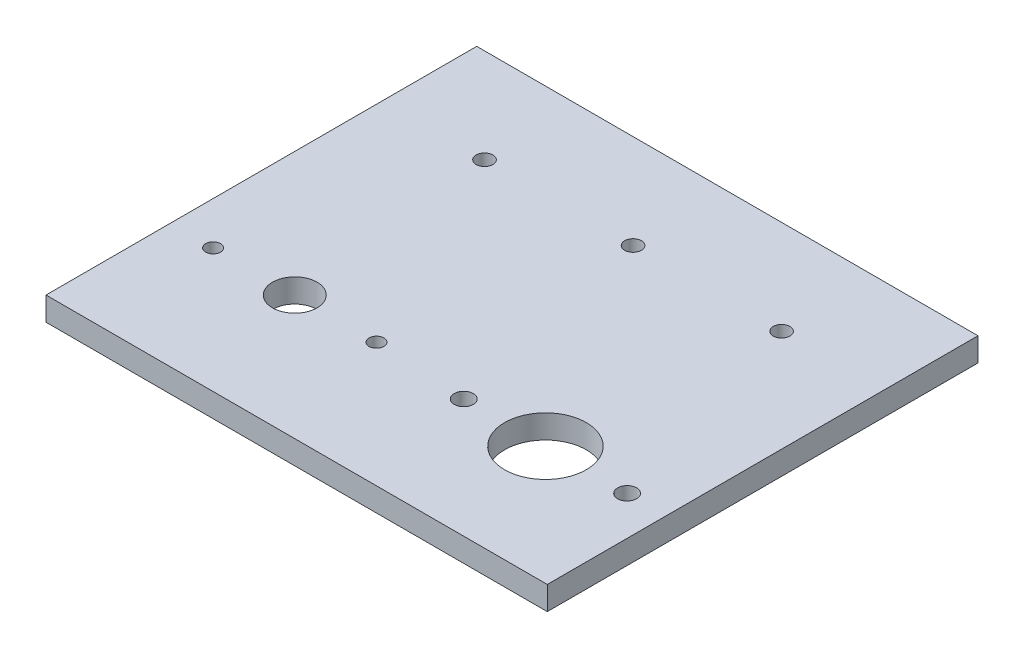
SolidWorks part; units mm, degrees
ref_plane "Front Plane" through (0, 0, 0) normal (0, 0, 1) x (1, 0, 0)
ref_plane "Top Plane" through (0, 0, 0) normal (0, 1, 0) x (1, 0, 0)
ref_plane "Right Plane" through (0, 0, 0) normal (1, 0, 0) x (0, 0, -1)
sketch "Sketch1" plane through (0, 0, 0) normal (0, 1, 0) x (1, 0, 0)
  line L1 (32.5, -58) -> (-32.5, -58)
  line L2 (32.5, -58) -> (32.5, 58)
  line L3 (32.5, 58) -> (-32.5, 58)
  line L4 (-32.5, -58) -> (-32.5, 58)
  line L5 (32.5, -58) -> (-32.5, 58) construction
  line L6 (32.5, 58) -> (-32.5, -58) construction
  line L7 (32.5, 7) -> (-32.5, 7) construction
  line L8 (32.5, 7) -> (32.5, 58) construction
  line L9 (32.5, 58) -> (-32.5, 58) construction
  line L10 (-32.5, 7) -> (-32.5, 58) construction
  line L11 (32.5, 7) -> (-32.5, 58) construction
  line L12 (32.5, 58) -> (-32.5, 7) construction
  line L13 (-102.5, -58) -> (-32.5, -58)
  line L14 (-102.5, -58) -> (-102.5, 58)
  line L15 (-102.5, 58) -> (-32.5, 58)
  line L16 (-32.5, -58) -> (-32.5, 58)
  line L17 (-102.5, -58) -> (-32.5, 58) construction
  line L18 (-102.5, 58) -> (-32.5, -58) construction
  point P0 (0, 0)
  point P6 (0, 32.5)
  point P7 (-67.5, 0)
  dimension "D1" = 51
  dimension "D2" = 65
  dimension "D3" = 65
  dimension "D4" = 70
extrude "Boss-Extrude1" add sketch "Sketch1" along normal blind 6.35 contours L4 L1 L2 L3 | L15 L14 L13 L4
sketch "Sketch2" plane through (0, 6.35, 0) normal (0, 1, 0) x (1, 0, 0)
  line L3 (32.5, -58) -> (-102.5, -58) construction
  circle A0 centre (0, -25.996) radius 22 construction
  circle A1 centre (-22, -25.996) radius 2.0193
  circle A2 centre (22, -25.996) radius 2.0193
  circle A3 centre (0, -25.996) radius 32.004 construction
  dimension "D1" = 44
  dimension "D2" = 64.008
  dimension "D3" = 4.0386
hole_wizard "#10 Clearance Hole1" positions "Sketch3" profile "Sketch4" hole size "#10" standard "ANSI Inch" end condition through all
sketch "Sketch3" plane through (0, 6.35, 0) normal (0, 1, 0) x (1, 0, 0)
  point P0 (-22, -25.996)
  point P3 (22, -25.996)
sketch "Sketch4" plane through (-22, 6.35, 25.996) normal (1, 0, 0) x (0, 0, 1)
  line L0 (0, 0) -> (0, 6.35)
  line L1 (0, 6.35) -> (2.5527, 6.35)
  line L2 (2.5527, 6.35) -> (2.5527, 0)
  line L5 (2.5527, 0) -> (0, 0)
  line L11 (0, -6.35) -> (0, 107.95) construction
  dimension "Thru Hole Dia." = 5.1054
  dimension "Thru Hole Depth" = 6.35
sketch "Sketch5" plane through (0, 6.35, 0) normal (0, 1, 0) x (1, 0, 0)
  line L0 (-75, 32.6) -> (-35, 32.6) construction
  line L1 (-35, 32.6) -> (5, 32.6) construction
  line L2 (32.5, 58) -> (-102.5, 58) construction
  point P9 (-35, 58)
  dimension "D1" = 40
  dimension "D2" = 40
  dimension "D3" = 25.4
sketch "Sketch9" plane through (0, 6.35, 0) normal (0, 1, 0) x (1, 0, 0)
  circle A0 centre (0, -25.996) radius 11
  circle A5 centre (0, -25.996) radius 22 construction
  dimension "D1" = 22
extrude "Cut-Extrude2" cut sketch "Sketch9" against normal through all
ref_plane "Plane1" through (-35, 0, 0) normal (-1, 0, 0) x (0, 0, 1)
hole_wizard "M4 Clearance Hole1" positions "Sketch10" profile "Sketch11" hole size "M4" standard "ANSI Metric" end condition through all
sketch "Sketch10" plane through (0, 6.35, 0) normal (0, 1, 0) x (1, 0, 0)
  point P0 (-75, 32.6)
  point P3 (-35, 32.6)
  point P6 (5, 32.6)
sketch "Sketch11" plane through (-75, 6.35, -32.6) normal (1, 0, 0) x (0, 0, 1)
  line L0 (0, 0) -> (0, 6.35)
  line L1 (0, 6.35) -> (2.25, 6.35)
  line L2 (2.25, 6.35) -> (2.25, 0)
  line L5 (2.25, 0) -> (0, 0)
  line L11 (0, -6.35) -> (0, 107.95) construction
  dimension "Thru Hole Dia." = 4.5
  dimension "Thru Hole Depth" = 6.35
sketch "Sketch12" plane through (0, 6.35, 0) normal (0, 1, 0) x (1, 0, 0)
  line L1 (32.5, -58) -> (-102.5, -58) construction
  line L2 (-102.5, -58) -> (-102.5, 58) construction
  circle A0 centre (-69, -24.5) radius 6
  circle A1 centre (-69, -24.5) radius 22 construction
  circle A2 centre (-91, -24.5) radius 2
  circle A3 centre (-47, -24.5) radius 2
  circle A6 centre (-69, -24.5) radius 33.5 construction
  circle A7 centre (0, -25.996) radius 11
  circle A8 centre (0, -25.996) radius 11 construction
  dimension "D1" = 12
  dimension "D2" = 4
  dimension "D3" = 4
  dimension "D4" = 44
  dimension "D6" = 67
  dimension "D5" = 0
extrude "Cut-Extrude3" cut sketch "Sketch12" against normal through all both
